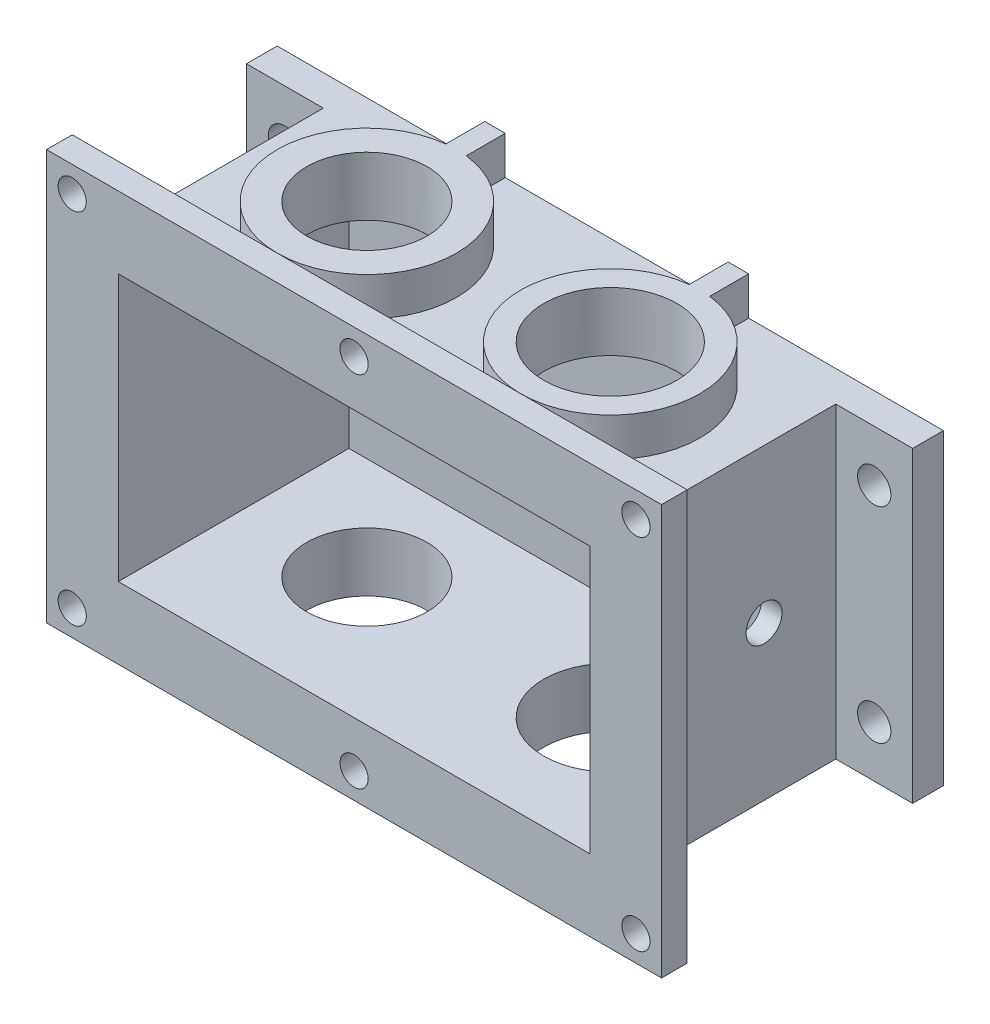
SolidWorks part; units mm, degrees
ref_plane "前视基准面" through (0, 0, 0) normal (0, 0, 1) x (1, 0, 0)
ref_plane "上视基准面" through (0, 0, 0) normal (0, 1, 0) x (1, 0, 0)
ref_plane "右视基准面" through (0, 0, 0) normal (1, 0, 0) x (0, 0, -1)
sketch "草图1" plane through (0, 0, 0) normal (0, 0, 1) x (1, 0, 0)
  line L0 (-100, -60) -> (100, -60)
  line L1 (100, -60) -> (100, 60)
  line L2 (100, 60) -> (-100, 60)
  line L3 (-100, 60) -> (-100, -60)
extrude "凸台-拉伸1" add sketch "草图1" along normal blind 100
ref_plane "基准面1" through (0, 0, 10) normal (0, 0, 1) x (1, 0, 0)
sketch "草图2" plane through (0, 0, 10) normal (0, 0, 1) x (1, 0, 0)
  line L0 (-92, -52) -> (92, -52)
  line L1 (92, -52) -> (92, 52)
  line L2 (92, 52) -> (-92, 52)
  line L3 (-92, 52) -> (-92, -52)
extrude "切除-拉伸1" cut sketch "草图2" along normal blind 90
ref_plane "基准面2" through (0, 55, 0) normal (0, 1, 0) x (1, 0, 0)
sketch "草图3" plane through (0, 55, 0) normal (0, 1, 0) x (1, 0, 0)
  circle A0 centre (-45, -50) radius 35
  circle A1 centre (50, -50) radius 35
extrude "凸台-拉伸2" add sketch "草图3" along normal blind 20
ref_plane "基准面3" through (0, -55, 0) normal (0, 1, 0) x (1, 0, 0)
sketch "草图4" plane through (0, -55, 0) normal (0, 1, 0) x (1, 0, 0)
  circle A0 centre (-45, -50) radius 35
  circle A1 centre (50, -50) radius 35
extrude "凸台-拉伸3" add sketch "草图4" against normal blind 20
sketch "草图5" plane through (0, 55, 0) normal (0, 1, 0) x (1, 0, 0)
  line L0 (-49, 0) -> (-41, 0)
  line L1 (-41, 0) -> (-41, -25)
  line L2 (-41, -25) -> (-49, -25)
  line L3 (-49, -25) -> (-49, 0)
  line L4 (46, 0) -> (54, 0)
  line L5 (54, 0) -> (54, -25)
  line L6 (54, -25) -> (46, -25)
  line L7 (46, -25) -> (46, 0)
extrude "凸台-拉伸4" add sketch "草图5" along normal blind 20
sketch "草图6" plane through (0, -55, 0) normal (0, 1, 0) x (1, 0, 0)
  line L0 (-49, 0) -> (-41, 0)
  line L1 (-41, 0) -> (-41, -25)
  line L2 (-41, -25) -> (-49, -25)
  line L3 (-49, -25) -> (-49, 0)
  line L4 (46, 0) -> (54, 0)
  line L5 (54, 0) -> (54, -25)
  line L6 (54, -25) -> (46, -25)
  line L7 (46, -25) -> (46, 0)
extrude "凸台-拉伸5" add sketch "草图6" against normal blind 20
sketch "草图7" plane through (0, 0, 0) normal (0, 0, 1) x (1, 0, 0)
  line L0 (100, -60) -> (130, -60)
  line L1 (130, -60) -> (130, 60)
  line L2 (130, 60) -> (100, 60)
  line L3 (100, 60) -> (100, -60)
  line L4 (-130, -60) -> (-100, -60)
  line L5 (-100, -60) -> (-100, 60)
  line L6 (-100, 60) -> (-130, 60)
  line L7 (-130, 60) -> (-130, -60)
extrude "凸台-拉伸6" add sketch "草图7" along normal blind 12
ref_plane "基准面4" through (0, 0, 90) normal (0, 0, 1) x (1, 0, 0)
sketch "草图8" plane through (0, 0, 90) normal (0, 0, 1) x (1, 0, 0)
  line L0 (-120, -80) -> (120, -80)
  line L1 (120, -80) -> (120, 80)
  line L2 (120, 80) -> (-120, 80)
  line L3 (-120, 80) -> (-120, -80)
  line L4 (-92, -52) -> (92, -52)
  line L5 (92, -52) -> (92, 52)
  line L6 (92, 52) -> (-92, 52)
  line L7 (-92, 52) -> (-92, -52)
extrude "凸台-拉伸7" add sketch "草图8" along normal blind 10
sketch "草图9" plane through (0, 0, 90) normal (0, 0, 1) x (1, 0, 0)
  circle A0 centre (-110, 70) radius 5.5
  circle A1 centre (110, 70) radius 5.5
  circle A2 centre (-110, -70) radius 5.5
  circle A3 centre (110, -70) radius 5.5
  circle A4 centre (0, 70) radius 5.5
  circle A5 centre (0, -70) radius 5.5
extrude "切除-拉伸2" cut sketch "草图9" along normal blind 10
ref_plane "基准面5" through (0, 75, 0) normal (0, 1, 0) x (1, 0, 0)
sketch "草图10" plane through (0, 75, 0) normal (0, 1, 0) x (1, 0, 0)
  circle A0 centre (-45, -50) radius 23.5
extrude "切除-拉伸3" cut sketch "草图10" against normal through all
sketch "草图11" plane through (0, 75, 0) normal (0, 1, 0) x (1, 0, 0)
  circle A0 centre (50, -50) radius 26
extrude "切除-拉伸4" cut sketch "草图11" against normal through all
sketch "草图12" plane through (0, 0, 0) normal (0, 0, 1) x (1, 0, 0)
  circle A0 centre (0, 0) radius 5.1
extrude "切除-拉伸5" cut sketch "草图12" along normal blind 10
ref_plane "基准面6" through (100, 0, 0) normal (1, 0, 0) x (0, 0, -1)
sketch "草图14" plane through (0, 0, 0) normal (0, 0, 1) x (1, 0, 0)
  circle A0 centre (115, 40) radius 6.5
  circle A1 centre (115, -40) radius 6.5
  circle A2 centre (-115, 40) radius 6.5
  circle A3 centre (-115, -40) radius 6.5
extrude "切除-拉伸7" cut sketch "草图14" along normal blind 12
sketch "草图15" plane through (100, 0, 0) normal (1, 0, 0) x (0, 0, -1)
  circle A0 centre (-40, 0) radius 7
extrude "切除-拉伸8" cut sketch "草图15" against normal blind 8
